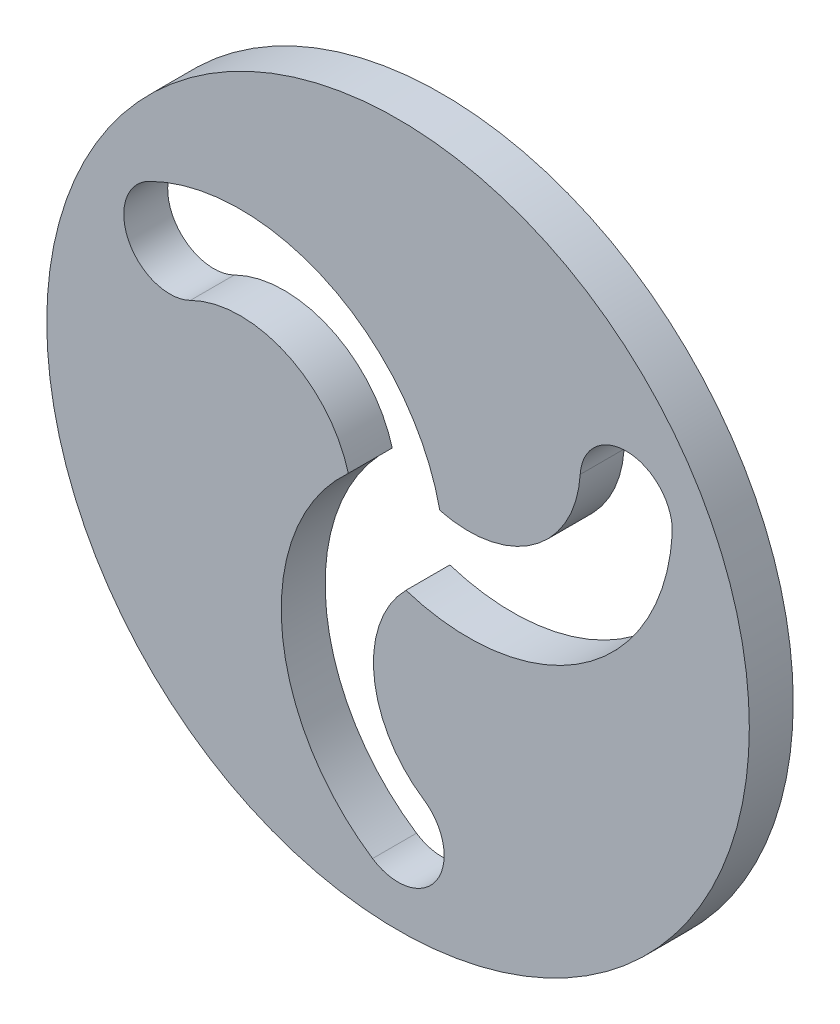
SolidWorks part; units mm, degrees
ref_plane "Alzado" through (0, 0, 0) normal (0, 0, 1) x (1, 0, 0)
ref_plane "Planta" through (0, 0, 0) normal (0, 1, 0) x (1, 0, 0)
ref_plane "Vista lateral" through (0, 0, 0) normal (1, 0, 0) x (0, 0, -1)
sketch "Croquis1" plane through (0, 0, 0) normal (0, 0, 1) x (1, 0, 0)
  circle A0 centre (0, 0) radius 40
  dimension "D1" = 80
extrude "Disco" add sketch "Croquis1" along normal blind 5
sketch "Croquis6" plane through (0, 0, 5) normal (0, 0, 1) x (1, 0, 0)
  line L6 (0, 0) -> (0, -30) construction
  circle A7 centre (0, -30) radius 5.25
  circle A8 centre (0, 0) radius 5.25
  arc A9 (0, -30) -> (0, 0) centre (9.9499, -15) cw
  arc A10 (2.902, -25.625) -> (2.902, -4.375) centre (9.9499, -15) cw
  arc A11 (-2.902, -34.375) -> (-2.902, 4.375) centre (9.9499, -15) cw
  circle A12 centre (0, 0) radius 5.25
  arc A13 (-28.3186, 19.7007) -> (5.2399, 0.3257) centre (-17.9653, -1.1168) cw
  arc A14 (-23.6429, 10.2993) -> (-5.2399, -0.3257) centre (-17.9653, -1.1168) cw
  circle A15 centre (-25.9808, 15) radius 5.25
  circle A16 centre (0, 0) radius 5.25
  arc A17 (31.2206, 14.6743) -> (-2.3378, -4.7007) centre (8.0154, 16.1168) cw
  arc A18 (20.7409, 15.3257) -> (2.3378, 4.7007) centre (8.0154, 16.1168) cw
  circle A19 centre (25.9808, 15) radius 5.25
  point P22 (0, 0)
  point P33 (0, 0)
  dimension "D1" = 30
  dimension "D3" = 10.5
  dimension "D5" = 5.25
  dimension "D2" = 10.5
  dimension "D6" = 18
  dimension "D4" = 5.25
  dimension "D7" = 3
extrude "Cortar-Extruir1" cut sketch "Croquis6" against normal blind 10 contours A18 A13 A15 A14 A11 A16 | A19 A18 A13 A8 A10 A17 | A14 A11 A7 A9 A12 | L6 A17 A8 A9 A7 A10 | A11 A14 A8 | A13 A18 A12 | A8 L6 A17 A10 | L6 A16 A17 | A9 L6 A8 A12 A16 | L6 A9 A8 A16 | A10 L6 A7 | A17 L6 A10
